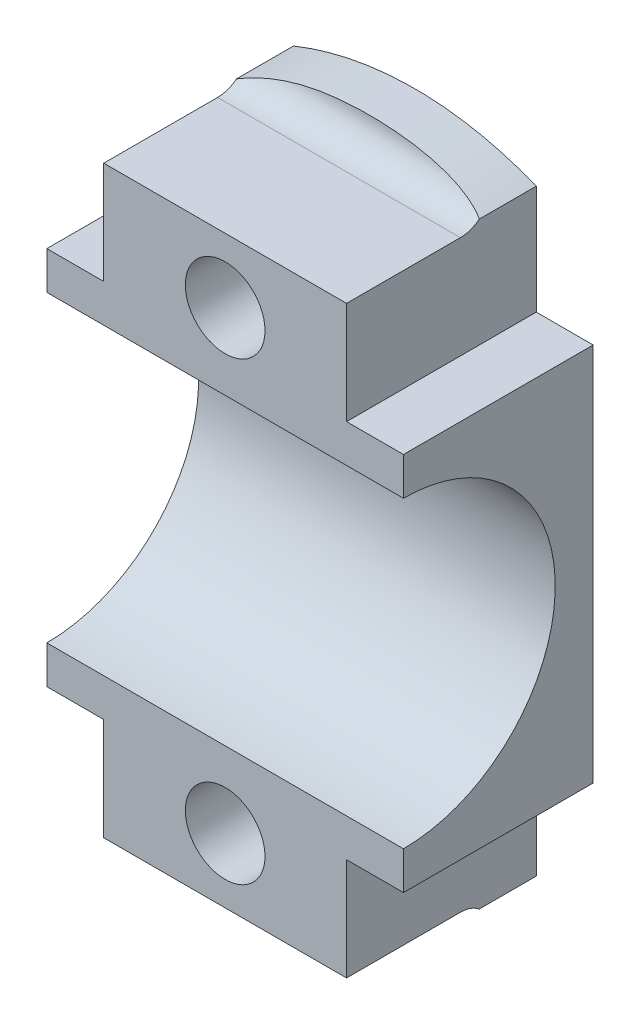
SolidWorks part; units mm, degrees
material "Brass"
ref_plane "Front Plane" through (0, 0, 0) normal (0, 0, 1) x (1, 0, 0)
ref_plane "Top Plane" through (0, 0, 0) normal (0, 1, 0) x (1, 0, 0)
ref_plane "Right Plane" through (0, 0, 0) normal (1, 0, 0) x (0, 0, -1)
sketch "Sketch1" plane through (0, 0, 0) normal (0, 0, 1) x (1, 0, 0)
  line L0 (0, 0) -> (0, -63047.302) construction
  line L1 (0, 0) -> (-63047.302, 0) construction
  line L2 (-47, -40) -> (47, -40)
  line L3 (32, 67.8307) -> (32, 50)
  line L4 (-47, 40) -> (-47, -40)
  line L5 (47, 40) -> (47, -40)
  line L6 (-47, 40) -> (47, 40)
  line L7 (32, 50) -> (47, 50)
  line L8 (-32, 67.8307) -> (-32, 78.7464)
  line L9 (32, 67.8307) -> (32, 78.7464)
  line L10 (-32, -67.8307) -> (-32, -78.7464)
  line L11 (32, -67.8307) -> (32, -78.7464)
  line L12 (47, 50) -> (47, 40)
  line L13 (-32, 67.8307) -> (-32, 50)
  line L14 (-32, 50) -> (-47, 50)
  line L15 (47, -50) -> (47, -40)
  line L16 (32, -50) -> (47, -50)
  line L17 (32, -67.8307) -> (32, -50)
  line L18 (-32, -50) -> (-47, -50)
  line L19 (-32, -67.8307) -> (-32, -50)
  line L20 (-47, -50) -> (-47, -40)
  line L21 (-47, 50) -> (-47, 40)
  circle A0 centre (0, -60) radius 10.5
  circle A1 centre (0, 60) radius 10.5
  arc A2 (32, 67.8307) -> (-32, 67.8307) centre (0, 0) ccw
  arc A3 (32, 78.7464) -> (-32, 78.7464) centre (0, 0) ccw
  arc A4 (-32, -67.8307) -> (32, -67.8307) centre (0, 0) ccw
  arc A5 (-32, -78.7464) -> (32, -78.7464) centre (0, 0) ccw
  point P14 (39.5, 50)
  point P15 (47, 45)
  point P17 (0, 43.5061)
  point P29 (-47, 45)
  point P30 (-39.5, 50)
  dimension "D1" = 21
  dimension "D3" = 150
  dimension "D4" = 170
  dimension "D2" = 120
  dimension "D5" = 80
  dimension "D6" = 94
  dimension "D7" = 10
  dimension "D8" = 32
extrude "Boss-Extrude1" add sketch "Sketch1" along normal blind 50 contours L9 A3 L8 A2 | L3 A2 L13 L14 L21 L6 L12 L7 A1 | L6 L4 L2 L5 | L19 A4 L17 L16 L15 L2 L20 L18 A0 | L10 A5 L11 A4
sketch "Sketch2" plane through (47, 0, 0) normal (1, 0, 0) x (0, 0, -1)
  line L0 (-50, 50) -> (-50, -50) construction
  line L1 (-50, 40) -> (-50, -40)
  line L2 (0, 0) -> (50000, 0) construction
  line L3 (0, 85) -> (-50, 85) construction
  line L4 (-50, -77) -> (-20, -77)
  line L7 (-50, 85) -> (-12, 85)
  line L8 (-12, 85) -> (-50, 85)
  line L9 (-50, 77) -> (-20, 77)
  line L10 (-50, 50) -> (-50, 78.7464) construction
  line L11 (-50, 85) -> (-50, 77)
  line L12 (-50, -85) -> (-50, -77)
  line L13 (-50, -85) -> (-12, -85)
  arc A0 (-50, -40) -> (-50, 40) centre (-50, 0) ccw
  arc A2 (-20, 77) -> (-12, 85) centre (-20, 85) ccw
  arc A3 (-20, -77) -> (-12, -85) centre (-20, -85) cw
  line M8 (-50, 50) -> (-50, -50)
  dimension "D1" = 80
  dimension "D2" = 8
  dimension "D3" = 8
  dimension "D4" = 12
extrude "Cut-Extrude1" cut sketch "Sketch2" against normal through all contours L9 A2 L7 L11 | A0 M8 | L2 A0 M8 | A3 L4 L12 L13
sketch "Sketch3" plane through (0, 0, 0) normal (0, 0, -1) x (-1, 0, 0)
  circle A0 centre (0, 0) radius 10
  dimension "D1" = 20
extrude "Boss-Extrude2" add sketch "Sketch3" along normal blind 5
